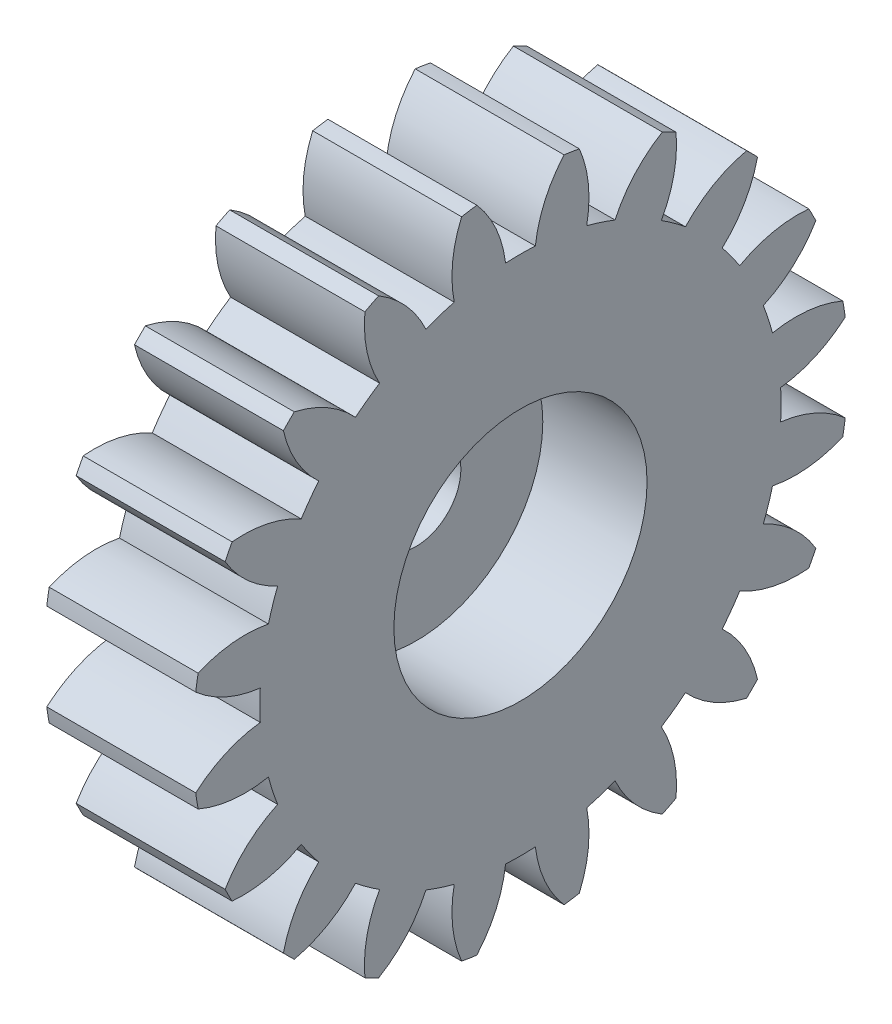
SolidWorks part; units mm, degrees
ref_plane "Plane1" through (0, 0, 0) normal (0, 0, 1) x (1, 0, 0)
ref_plane "Plane2" through (0, 0, 0) normal (0, 1, 0) x (1, 0, 0)
ref_plane "Plane3" through (0, 0, 0) normal (1, 0, 0) x (0, 0, -1)
other "Configuration Table"
sketch "HoldingSke" plane through (0, 0, 0) normal (0, 1, 0) x (1, 0, 0)
  line L0 (0, 0) -> (0.9397, -0.342)
  line L1 (-15, 0) -> (100, 0) construction
  line L2 (0, 0) -> (-2.1039, 2.3779)
  line L3 (0, 0) -> (-11.863, 4.5341)
  line L4 (0, 0) -> (8.1152, 2.9537)
  line L5 (0, 0) -> (-46.8476, -17.4728)
  line L6 (0, 0) -> (-4.1448, -2.7965)
  line L7 (-2.1039, 2.3779) -> (8.6586, 51.2059)
  line L8 (-76.2, 54.61) -> (-75.7, 54.61)
  line L9 (-71.009, 38.7566) -> (-53.1078, 45.2721)
  line L10 (-76.2, 71.12) -> (104.1128, 71.12)
  line L11 (0, 0) -> (-5, 0)
  line L12 (-76.2, 101.6) -> (-76.162, 101.6)
  line L13 (24.9733, 27.94) -> (52.9518, 28.4284)
  line L14 (24.9733, 27.94) -> (24.9743, 27.94)
  line L15 (24.9733, 27.94) -> (100.4006, 29.5858)
  line L16 (-63.627, -1) -> (-12.827, -1)
  circle A0 centre (0, 0) radius 1.5
  circle A1 centre (0, 0) radius 8.749
  circle A2 centre (0, 0) radius 37.5
  circle A3 centre (0, 0) radius 1.5
  dimension "MHD" = 17.498
  dimension "Hub_dia" = 75
  dimension "Bore" = 3
  dimension "MBD" = 3
  dimension "Num_teeth" = 20
  dimension "Pitch" = 1
  dimension "Overall_len" = 50
  dimension "Show_teeth" = 20
  dimension "Thickness" = 5
  dimension "OAL" = 50.0001
  dimension "T_dim" = 0.5
  dimension "Ap" = 20
  dimension "H" = 19.05
  dimension "Pitch_radius" = 180.3128
  dimension "Width" = 5
  dimension "Backlash" = 0.038
  dimension "Addendum_fac" = 1
  dimension "Dedendum_fac" = 1.25
  dimension "Clearance_fac" = 0.25
  dimension "Dedendum_add" = 0.001
  dimension "Module" = 1
sketch "BasProSke" plane through (0, 0, 0) normal (0, 1, 0) x (1, 0, 0)
  line L0 (-10, 0) -> (60, 0) construction
  line L1 (0, 0) -> (0, 11)
  line L2 (0, 0) -> (5, 0)
  line L3 (5, 0) -> (5, 11)
  line L4 (5, 11) -> (0, 11)
  dimension "Thickness" = 5
  dimension "Diameter" = 22
revolve "Base-Revolve" add sketch "BasProSke" angle 360 about L0
sketch "TooCutSke" plane through (0, 0, 0) normal (1, 0, 0) x (0, 0, -1)
  line L1 (0, 0) -> (0, 107) construction
  line L2 (0, 0) -> (-0.8511, 9.9637) construction
  line L3 (0, 0) -> (-3.1206, 19.7028) construction
  line L4 (-0.8511, 9.9637) -> (-1.5603, 9.8514) construction
  arc A0 (0.4999, 8.7347) -> (-0.4999, 8.7347) centre (0, 0) ccw
  arc A1 (1.4852, 10.9249) -> (-1.4852, 10.9249) centre (0, 0) ccw
  circle A2 centre (0, 0) radius 10 construction
  circle A3 centre (0, 0) radius 9.3969 construction
  arc A4 (-0.4999, 8.7347) -> (-1.4852, 10.9249) centre (-4.4722, 8.2645) ccw
  arc A5 (1.4852, 10.9249) -> (0.4999, 8.7347) centre (4.4722, 8.2645) ccw
  dimension "Root_dia" = 17.498
  dimension "Overcut_dia" = 22.0508
  dimension "Pitch_dia" = 20
  dimension "Base_dia" = 18.7939
  dimension "Flank_rad" = 4
  dimension "Half_ang" = 9
  dimension "Half_CT" = 0.7181
extrude "ToothCut" cut sketch "TooCutSke" along normal through all
fillet "Breaks" [suppressed] radius 0.02
fillet "RootFillets" [suppressed] radius 0.251
pattern_circular "TeethCuts" count 20 every 18 about axis through (-10, 0, 0) along (1, 0, 0) of "ToothCut", "RootFillets", "Breaks"
sketch "HubNeaOneSke" plane through (0, 0, 0) normal (-1, 0, 0) x (0, 0, 1)
  circle A0 centre (0, 0) radius 8.749
  dimension "Diameter" = 17.498
extrude "HubNearOne" [suppressed] add sketch "HubNeaOneSke" along normal blind 45.0001
sketch "HubNeaBotSke" plane through (0, 0, 0) normal (-1, 0, 0) x (0, 0, 1)
  circle A0 centre (0, 0) radius 8.749
  dimension "Diameter" = 17.498
extrude "HubNearBoth" [suppressed] add sketch "HubNeaBotSke" along normal blind 22.5
ref_plane "FarPln" through (5, 0, 0) normal (1, 0, 0) x (0, 0, -1)
sketch "HubFarSke" plane through (5, 0, 0) normal (1, 0, 0) x (0, 0, -1)
  circle A0 centre (0, 0) radius 8.749
  dimension "Diameter" = 17.498
extrude "HubFar" [suppressed] add sketch "HubFarSke" along normal blind 22.5
sketch "BorSke" plane through (0, 0, 0) normal (1, 0, 0) x (0, 0, -1)
  circle A0 centre (0, 0) radius 1.5
  dimension "Diameter" = 3
extrude "Bore" cut sketch "BorSke" along normal mid plane 100.0001
sketch "KeySke" plane through (0, 0, 0) normal (1, 0, 0) x (0, 0, -1)
  line L0 (-0.6, 0) -> (-0.6, 2)
  line L1 (-0.6, 2) -> (0.6, 2)
  line L2 (0.6, 2) -> (0.6, 0)
  line L3 (0, 0) -> (0, 34) construction
  line L4 (-0.6, 0) -> (0.6, 0)
  dimension "Offset" = 2
  dimension "Width" = 1.2
extrude "Keyway" [suppressed] cut sketch "KeySke" along normal mid plane 100.0001
pattern_circular "Keyway2" [suppressed] count 2 every 90 about axis through (-10, 0, 0) along (1, 0, 0)
sketch "Sketch1" plane through (5, 0, 0) normal (1, 0, 0) x (0, 0, -1)
  circle A0 centre (0, 0) radius 4.25
  dimension "D1" = 8.5
extrude "Cut-Extrude1" cut sketch "Sketch1" against normal blind 3.5
equation "' \"Module@HoldingSke\" = 6.35"
equation "' \"Num_teeth@HoldingSke\" = 12"
equation "' \"Ap@HoldingSke\" =  20"
equation "' \"Ap@HoldingSke\" = 20"
equation "' \"Width@HoldingSke\" = 0.5 * 25.4"
equation "' \"Hub_dia@HoldingSke\"= 1 * 25.4"
equation "' \"Hub_dia@HoldingSke\" = 1 * 25.4"
equation "' \"Overall_len@HoldingSke\" = 1.0 * 25.4"
equation "' \"Bore@HoldingSke\" = 0.75 * 25.4"
equation "' \"T_dim@HoldingSke\" = 0.1 * 25.4"
equation "' \"Width@KeySke\" = 0.25 * 25.4"
equation "' \"Show_teeth@HoldingSke\" = 13"
equation "' \"Backlash@HoldingSke\" = 0.009 * 25.4"
equation "' \"Addendum_fac@HoldingSke\" = 1.0"
equation "' \"Dedendum_fac@HoldingSke\" = 1.25"
equation "' \"Dedendum_add@HoldingSke\" = 0.00005 * 25.4"
equation "' \"Clearance_fac@HoldingSke\" = 0.25"
equation "\"Pitch@HoldingSke\" = 1 / \"Module@HoldingSke\""
equation "\"Overcut_dia@TooCutSke\" = (\"Num_teeth@HoldingSke\" + 2 * \"Addendum_fac@HoldingSke\") / \"Pitch@HoldingSke\" + 0.002 * 25.4"
equation "\"Pitch_dia@TooCutSke\" = \"Num_teeth@HoldingSke\" / \"Pitch@HoldingSke\""
equation "\"Base_dia@TooCutSke\" = \"Num_teeth@HoldingSke\" / \"Pitch@HoldingSke\" * cos((\"Ap@HoldingSke\"  * 3.14159265 / 180))"
equation "\"Root_dia@TooCutSke\" = (\"Num_teeth@HoldingSke\" + 2) / \"Pitch@HoldingSke\" - 2 * (\"Addendum_fac@HoldingSke\" + \"Dedendum_fac@HoldingSke\") / \"Pitch@HoldingSke\" - \"Dedendum_add@HoldingSke\" * 2"
equation "\"Half_ang@TooCutSke\" = 180 / \"Num_teeth@HoldingSke\""
equation "\"Half_CT@TooCutSke\" = \"Num_teeth@HoldingSke\" / \"Pitch@HoldingSke\" * sin((3.14159265 / 2 / \"Num_teeth@HoldingSke\")) / 2 - 7 * \"Backlash@HoldingSke\" / 4"
equation "\"Flank_rad@TooCutSke\" = \"Num_teeth@HoldingSke\" / \"Pitch@HoldingSke\" / 5"
equation "\"Radius@RootFillets\" = \"Clearance_fac@HoldingSke\" / \"Pitch@HoldingSke\" + \"Dedendum_add@HoldingSke\""
equation "\"Break_rad@Breaks\" = 0.02 / \"Pitch@HoldingSke\""
equation "\"Thickness@HoldingSke\" = \"Width@HoldingSke\""
equation "\"OAL@HoldingSke\" = \"Thickness@HoldingSke\""
equation "\"MHD@HoldingSke\" = (\"Num_teeth@HoldingSke\" + 2) / \"Pitch@HoldingSke\" - 2 * (\"Addendum_fac@HoldingSke\" + \"Dedendum_fac@HoldingSke\")  / \"Pitch@HoldingSke\" - \"Dedendum_add@HoldingSke\" * 2"
equation "\"MBD@HoldingSke\" = (\"Num_teeth@HoldingSke\" + 2) / \"Pitch@HoldingSke\" - 2 * (\"Addendum_fac@HoldingSke\" + \"Dedendum_fac@HoldingSke\")  / \"Pitch@HoldingSke\" - \"Dedendum_add@HoldingSke\" * 2 - 0.002 * 25.4"
equation "\"MHD@HoldingSke\" = ((sgn( \"MHD@HoldingSke\" - \"Hub_dia@HoldingSke\" )-1)*( \"MHD@HoldingSke\" - \"Hub_dia@HoldingSke\" ))/-2+ \"Hub_dia@HoldingSke\""
equation "\"MBD@HoldingSke\" = ((sgn( \"MBD@HoldingSke\" - \"Bore@HoldingSke\" )-1)*( \"MBD@HoldingSke\" - \"Bore@HoldingSke\" ))/-2+ \"Bore@HoldingSke\""
equation "\"OAL@HoldingSke\" = ((sgn( \"OAL@HoldingSke\" - \"Overall_len@HoldingSke\" )+1)*( \"OAL@HoldingSke\" - \"Overall_len@HoldingSke\" ))/2 + \"Overall_len@HoldingSke\" + 0.000002 * 25.4"
equation "\"Num_teeth@TeethCuts\" = int( \"Show_teeth@HoldingSke\" ) + 1"
equation "\"Num_teeth@TeethCuts\" = ((sgn( \"Num_teeth@TeethCuts\" - \"Num_teeth@HoldingSke\" )-1)*( \"Num_teeth@TeethCuts\" - \"Num_teeth@HoldingSke\" ))/-2+ \"Num_teeth@HoldingSke\""
equation "\"Num_teeth@TeethCuts\" = ((sgn( \"Num_teeth@TeethCuts\" - 2.0)+1)*( \"Num_teeth@TeethCuts\" - 2.0))/2 +2.0"
equation "\"Angle@TeethCuts\" = 360.0 / \"Num_teeth@HoldingSke\""
equation "\"Diameter@BasProSke\" = (\"Num_teeth@HoldingSke\" + 2 * \"Addendum_fac@HoldingSke\") / \"Pitch@HoldingSke\""
equation "\"Thickness@BasProSke\"  = \"Thickness@HoldingSke\""
equation "' \"Fillet_rad@BasProSke\" =  \"Thickness@HoldingSke\" * 0.05"
equation "' \"Fillet_rad@BasProSke\" = \"Thickness@HoldingSke\" * 0.05"
equation "\"MHD@HoldingSke\" = ((sgn( \"MHD@HoldingSke\" - \"Root_dia@TooCutSke\" )-1)*( \"MHD@HoldingSke\" - \"Root_dia@TooCutSke\" ))/-2+ \"Root_dia@TooCutSke\""
equation "\"Diameter@HubNeaOneSke\" = \"MHD@HoldingSke\""
equation "\"Length@HubNearOne\" = \"OAL@HoldingSke\" - \"Thickness@BasProSke\""
equation "\"Diameter@HubNeaBotSke\" = \"MHD@HoldingSke\""
equation "\"Length@HubNearBoth\" = ( \"OAL@HoldingSke\" - \"Thickness@BasProSke\" ) / 2.0"
equation "\"Thickness@FarPln\" = \"Thickness@BasProSke\""
equation "\"Diameter@HubFarSke\" = \"MHD@HoldingSke\""
equation "\"Length@HubFar\" = ( \"OAL@HoldingSke\" - \"Thickness@BasProSke\" ) / 2.0"
equation "\"Diameter@BorSke\" = \"MBD@HoldingSke\""
equation "\"D1@Bore\" = \"OAL@HoldingSke\" * 2.0"
equation "\"D1@Keyway\" = \"OAL@HoldingSke\" * 2.0"
equation "\"Offset@KeySke\" = \"T_dim@HoldingSke\" + \"MBD@HoldingSke\" / 2.0"
